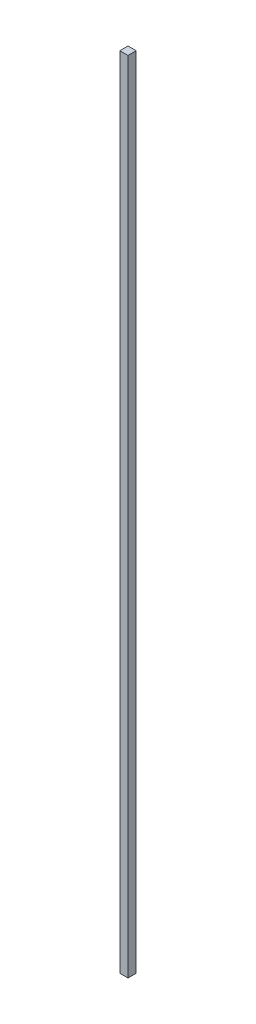
SolidWorks part; units mm, degrees
material "Balsa"
ref_plane "Front Plane" through (0, 0, 0) normal (0, 0, 1) x (1, 0, 0)
ref_plane "Top Plane" through (0, 0, 0) normal (0, 1, 0) x (1, 0, 0)
ref_plane "Right Plane" through (0, 0, 0) normal (1, 0, 0) x (0, 0, -1)
sketch "Sketch1" plane through (0, 0, 0) normal (0, 1, 0) x (1, 0, 0)
  line L1 (-1.5875, 1.5875) -> (1.5875, 1.5875)
  line L2 (-1.5875, 1.5875) -> (-1.5875, -1.5875)
  line L3 (-1.5875, -1.5875) -> (1.5875, -1.5875)
  line L4 (1.5875, 1.5875) -> (1.5875, -1.5875)
  line L5 (0, -1.5875) -> (0, 1.5875) construction
  line L6 (-1.5875, 0) -> (1.5875, 0) construction
  point P0 (0, 0)
  dimension "D1" = 3.175
extrude "Boss-Extrude1" add sketch "Sketch1" along normal blind 310
